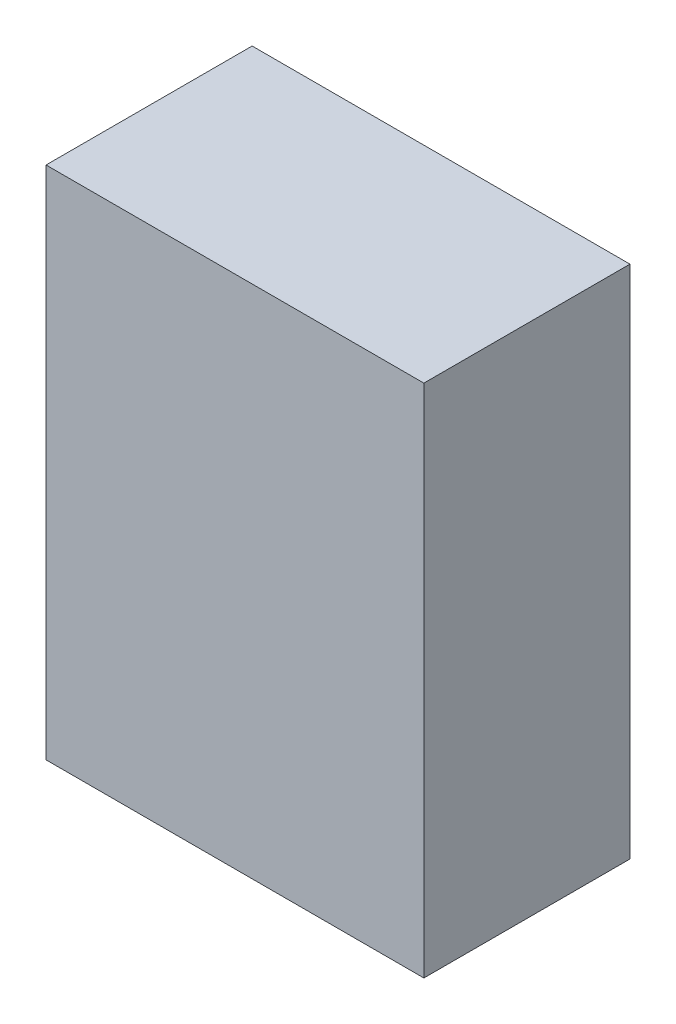
SolidWorks part; units mm, degrees
ref_plane "Front Plane" through (0, 0, 0) normal (0, 0, 1) x (1, 0, 0)
ref_plane "Top Plane" through (0, 0, 0) normal (0, 1, 0) x (1, 0, 0)
ref_plane "Right Plane" through (0, 0, 0) normal (1, 0, 0) x (0, 0, -1)
sketch "Sketch1" plane through (0, 0, 0) normal (0, 1, 0) x (1, 0, 0)
  line L1 (0, 0) -> (22, 0)
  line L2 (0, 0) -> (0, 12)
  line L3 (0, 12) -> (22, 12)
  line L4 (22, 0) -> (22, 12)
  dimension "D1" = 12
  dimension "D2" = 22
extrude "Boss-Extrude1" add sketch "Sketch1" along normal blind 30
